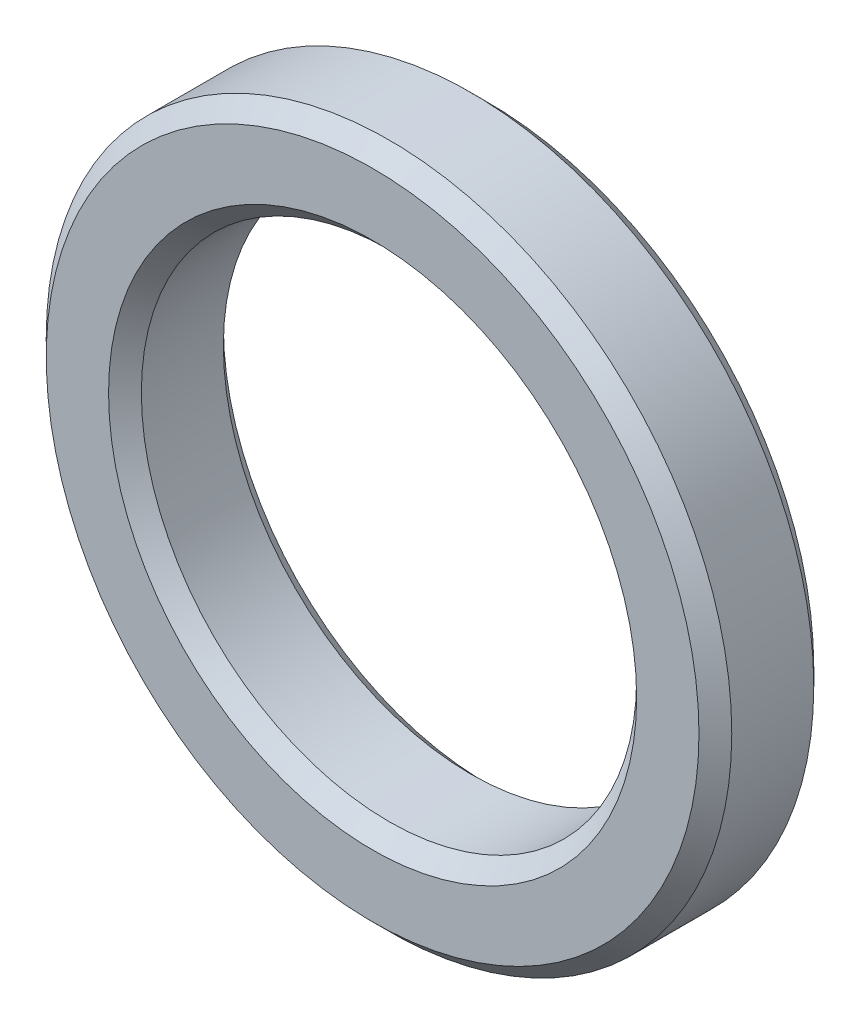
SolidWorks part; units mm, degrees
ref_plane "Front Plane" through (0, 0, 0) normal (0, 0, 1) x (1, 0, 0)
ref_plane "Top Plane" through (0, 0, 0) normal (0, 1, 0) x (1, 0, 0)
ref_plane "Right Plane" through (0, 0, 0) normal (1, 0, 0) x (0, 0, -1)
sketch "Sketch1" plane through (0, 0, 0) normal (1, 0, 0) x (0, 0, -1)
  line L0 (0, 0) -> (7, 0) construction
  line L1 (1, 15.1) -> (0, 16.1)
  line L2 (0, 16.1) -> (0, 19.9)
  line L3 (0, 19.9) -> (1, 20.9)
  line L4 (1, 20.9) -> (6, 20.9)
  line L5 (6, 20.9) -> (7, 19.9)
  line L6 (7, 19.9) -> (7, 16.1)
  line L7 (7, 16.1) -> (6, 15.1)
  line L8 (6, 15.1) -> (1, 15.1)
  dimension "D1" = 7
  dimension "D2" = 45
  dimension "D3" = 1
  dimension "D4" = 1
  dimension "D5" = 1
  dimension "D6" = 1
  dimension "D7" = 15.1
  dimension "D8" = 20.9
revolve "Revolve1" add sketch "Sketch1" angle 360 about L0
